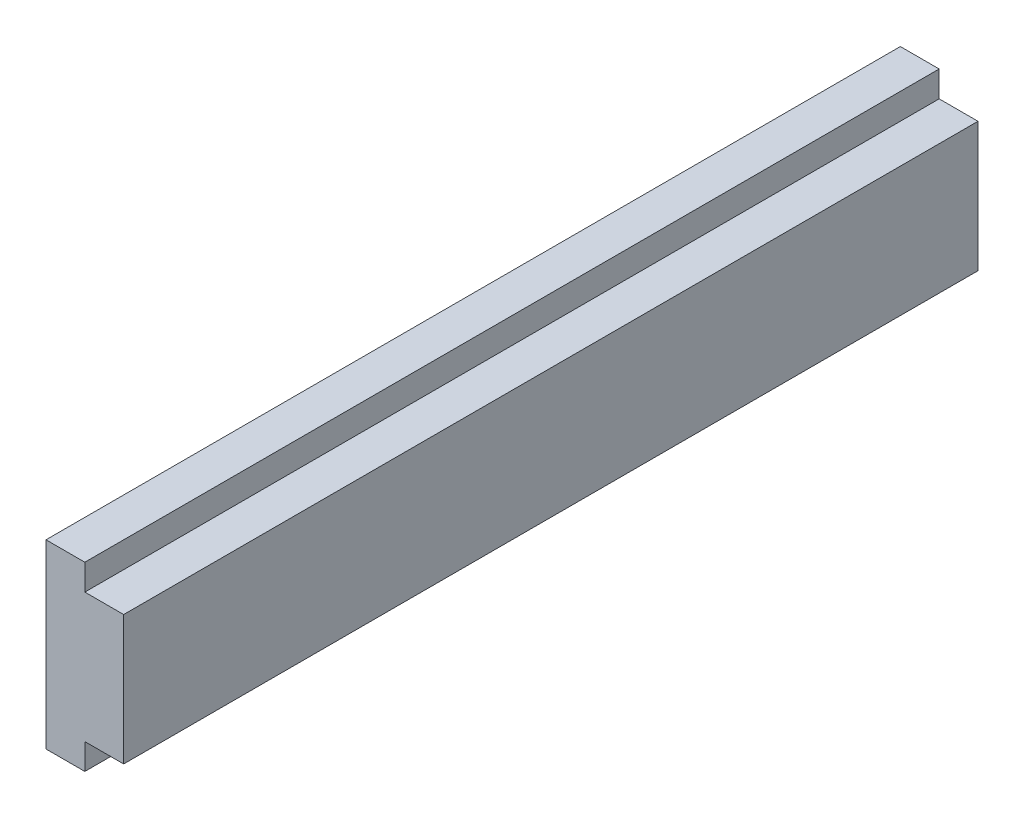
SolidWorks part; units mm, degrees
ref_plane "정면" through (0, 0, 0) normal (0, 0, 1) x (1, 0, 0)
ref_plane "윗면" through (0, 0, 0) normal (0, 1, 0) x (1, 0, 0)
ref_plane "우측면" through (0, 0, 0) normal (1, 0, 0) x (0, 0, -1)
sketch "스케치1" plane through (0, 0, 0) normal (0, 0, 1) x (1, 0, 0)
  line L1 (0, 0) -> (3, 0)
  line L2 (0, 0) -> (0, 14)
  line L3 (0, 14) -> (3, 14)
  line L4 (3, 0) -> (3, 14)
  line L5 (3, 12) -> (6, 12)
  line L6 (3, 12) -> (3, 2)
  line L7 (3, 2) -> (6, 2)
  line L8 (6, 12) -> (6, 2)
  dimension "D1" = 2
  dimension "D2" = 3
  dimension "D3" = 2
  dimension "D4" = 3
  dimension "D5" = 14
extrude "보스-돌출1" add sketch "스케치1" along normal blind 66 contours L1 L4 L3 L2 | L8 L5 L4 L7
